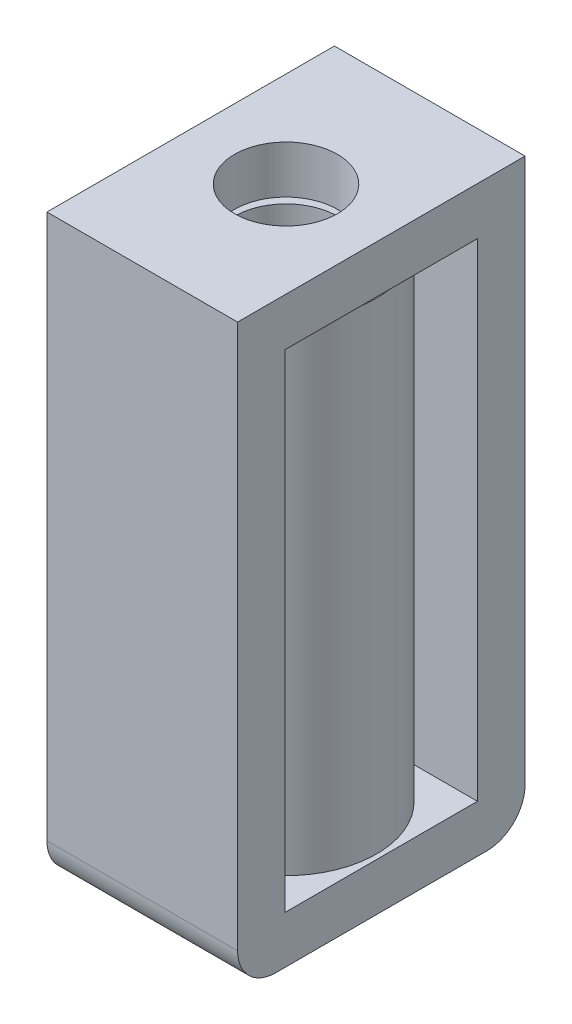
SolidWorks part; units mm, degrees
ref_plane "Front" through (0, 0, 0) normal (0, 0, 1) x (1, 0, 0)
ref_plane "Top" through (0, 0, 0) normal (0, 1, 0) x (1, 0, 0)
ref_plane "Right" through (0, 0, 0) normal (1, 0, 0) x (0, 0, -1)
sketch "Sketch1" plane through (0, 0, 0) normal (0, 1, 0) x (1, 0, 0)
  line L1 (-5, -7.54) -> (5, -7.54)
  line L2 (-5, -7.54) -> (-5, 7.54)
  line L3 (-5, 7.54) -> (5, 7.54)
  line L4 (5, -7.54) -> (5, 7.54)
  line L5 (-5, -7.54) -> (5, 7.54) construction
  line L6 (-5, 7.54) -> (5, -7.54) construction
  point P0 (0, 0)
  dimension "D1" = 15.08
  dimension "D2" = 10
extrude "Boss-Extrude1" add sketch "Sketch1" along normal blind 30.56
sketch "Sketch2" plane through (5, 0, 0) normal (1, 0, 0) x (0, 0, -1)
  line L0 (-7.54, 30.56) -> (-7.54, 0) construction
  line L1 (-5.04, 2.5) -> (5.04, 2.5)
  line L2 (-5.04, 2.5) -> (-5.04, 28.06)
  line L3 (-5.04, 28.06) -> (5.04, 28.06)
  line L4 (5.04, 2.5) -> (5.04, 28.06)
  line L5 (-5.04, 2.5) -> (5.04, 28.06) construction
  line L6 (-5.04, 28.06) -> (5.04, 2.5) construction
  line L7 (-7.54, 30.56) -> (7.54, 30.56) construction
  line L8 (7.54, 30.56) -> (7.54, 0) construction
  line L9 (-7.54, 0) -> (7.54, 0) construction
  point P0 (0, 15.28)
  dimension "D1" = 2.5
  dimension "D2" = 2.5
  dimension "D3" = 2.5
  dimension "D4" = 2.5
extrude "Cut-Extrude1" cut sketch "Sketch2" against normal blind 20
sketch "Sketch5" plane through (0, 2.5, 0) normal (0, 1, 0) x (1, 0, 0)
  circle A0 centre (0, 0) radius 4.75
  dimension "D1" = 9.5
extrude "Boss-Extrude2" add sketch "Sketch5" along normal blind 25.25
sketch "Sketch3" plane through (0, 30.56, 0) normal (0, 1, 0) x (1, 0, 0)
  circle A0 centre (0, 0) radius 2.7
  dimension "D1" = 5.4
extrude "Cut-Extrude2" cut sketch "Sketch3" against normal blind 20
fillet "Fillet1" radius 2 2 edges at (0, 0, -7.54) (0, 0, 7.54)
sketch "Sketch4" plane through (0, 0, -7.54) normal (0, 0, -1) x (-1, 0, 0)
  line L0 (-5, 30.56) -> (5, 30.56) construction
  line L1 (5, 0) -> (-5, 0) construction
  circle A0 centre (0, 22.26) radius 0.8
  circle A1 centre (0, 5.2) radius 0.8
  dimension "D1" = 1.6
  dimension "D2" = 8.3
  dimension "D3" = 5.2
extrude "Cut-Extrude3" cut sketch "Sketch4" against normal up to next
